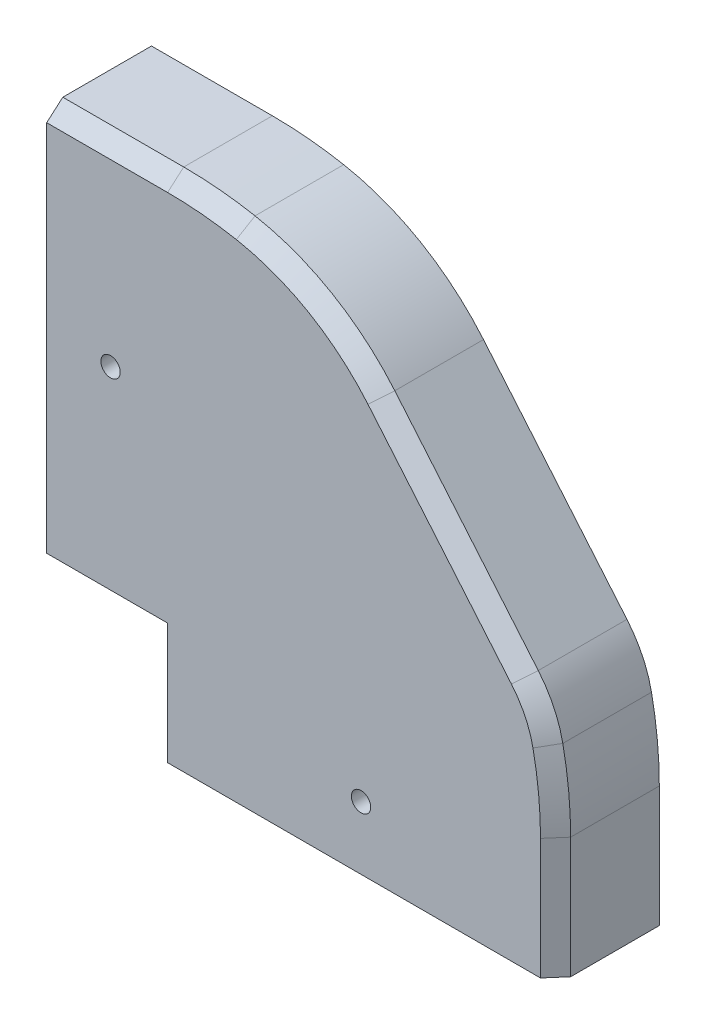
SolidWorks part; units mm, degrees
ref_plane "Front Plane" through (0, 0, 0) normal (0, 0, 1) x (1, 0, 0)
ref_plane "Top Plane" through (0, 0, 0) normal (0, 1, 0) x (1, 0, 0)
ref_plane "Right Plane" through (0, 0, 0) normal (1, 0, 0) x (0, 0, -1)
sketch "Sketch1" plane through (0, 0, 0) normal (0, 1, 0) x (1, 0, 0)
  line L0 (-30.48, 8.255) -> (30.48, 8.255)
  line L1 (-25.4, 3.175) -> (25.4, 3.175)
  line L2 (-25.4, 3.175) -> (-25.4, -3.175)
  line L3 (-25.4, -3.175) -> (25.4, -3.175)
  line L4 (25.4, 3.175) -> (25.4, -3.175)
  line L5 (-25.4, 3.175) -> (25.4, -3.175) construction
  line L6 (-25.4, -3.175) -> (25.4, 3.175) construction
  line L7 (30.48, 8.255) -> (30.48, -8.255)
  line L8 (-30.48, -8.255) -> (30.48, -8.255)
  line L9 (-30.48, 8.255) -> (-30.48, -8.255)
  point P0 (0, 0)
  dimension "D1" = 50.8
  dimension "D2" = 6.35
  dimension "D3" = 5.08
extrude "Boss-Extrude1" add sketch "Sketch1" along normal blind 19.05
sketch "Sketch2" plane through (0, 0, 8.255) normal (0, 0, 1) x (1, 0, 0)
  line L0 (-30.48, 19.05) -> (-30.48, 80.01)
  line L1 (-30.48, 19.05) -> (30.48, 19.05)
  arc A0 (30.48, 19.05) -> (-30.48, 80.01) centre (-30.48, 19.05) ccw
extrude "Boss-Extrude2" add sketch "Sketch2" against normal up to surface (16.51 mm away) up to face at (0, 9.525, -8.255)
ref_plane "Plane1" [suppressed] through (-24.765, 24.765, 0) normal (-0.7071, 0.7071, 0) x (0.7071, 0.7071, 0)
mirror "Mirror1" about plane through (-24.765, 24.765, 0) normal (-0.7071, 0.7071, 0) of "Boss-Extrude1"
sketch "Sketch5" plane through (0, 0, -8.255) normal (0, 0, -1) x (-1, 0, 0)
  line L0 (-2.7782, 66.1091) -> (-28.0617, 36.0498)
  circle A0 centre (0, 9.9172) radius 1.524
  circle A1 centre (39.4688, 49.53) radius 1.524
  arc A2 (30.48, 80.01) -> (-30.48, 19.05) centre (30.48, 19.05) ccw construction
  arc A3 (19.2423, 78.9652) -> (-28.0617, 36.0498) centre (30.48, 19.05) ccw
  arc A4 (19.2423, 78.9652) -> (-2.7782, 66.1091) centre (26.2299, 41.7097) ccw
  dimension "D1" = 3.048
  dimension "D2" = 3.048
extrude "Cut-Extrude1" cut sketch "Sketch5" against normal through all
chamfer "Chamfer1" distance 2.1082 angle 41 2 edges at (-40.9928, 49.53, -8.255) (-1.524, 9.9172, -8.255)
fillet "Fillet1" radius 18.034 1 edges at (28.0617, 36.0498, 0)
chamfer "Chamfer2" distance 2.54 angle 41 7 edges at (30.48, 9.525, 8.255) (30.1718, 25.1719, 8.255) (27.8168, 35.4764, 8.255) (14.0797, 52.6728, 8.255) (-7.1186, 74.4444, 8.255) (-40.005, 80.01, 8.255) (-24.8369, 79.7482, 8.255)
sketch "Sketch6" plane through (0, 0, 0) normal (0, -1, 0) x (1, 0, 0)
  line L14 (26.035, -3.81) -> (26.035, 3.81)
  line L15 (-26.035, -3.81) -> (26.035, -3.81)
  line L16 (-26.035, 3.81) -> (-26.035, -3.81)
  line L17 (26.035, 3.81) -> (-26.035, 3.81)
  line L18 (26.035, -3.81) -> (26.035, 3.81)
  line L19 (-26.035, -3.81) -> (26.035, -3.81)
  line L20 (-26.035, 3.81) -> (-26.035, -3.81)
  line L21 (26.035, 3.81) -> (-26.035, 3.81)
  dimension "D1" = 0.635
extrude "Cut-Extrude2" cut sketch "Sketch6" against normal blind 19.05
sketch "Sketch7" plane through (-49.53, 0, 0) normal (-1, 0, 0) x (0, 0, 1)
  line L15 (-3.81, 23.495) -> (3.81, 23.495)
  line L16 (-3.81, 75.565) -> (-3.81, 23.495)
  line L17 (3.81, 23.495) -> (3.81, 75.565)
  line L18 (3.81, 75.565) -> (-3.81, 75.565)
  line L19 (-3.81, 23.495) -> (3.81, 23.495)
  line L20 (-3.81, 75.565) -> (-3.81, 23.495)
  line L21 (3.81, 23.495) -> (3.81, 75.565)
  line L22 (3.81, 75.565) -> (-3.81, 75.565)
  dimension "D1" = 0.635
extrude "Cut-Extrude3" cut sketch "Sketch7" against normal blind 19.05
